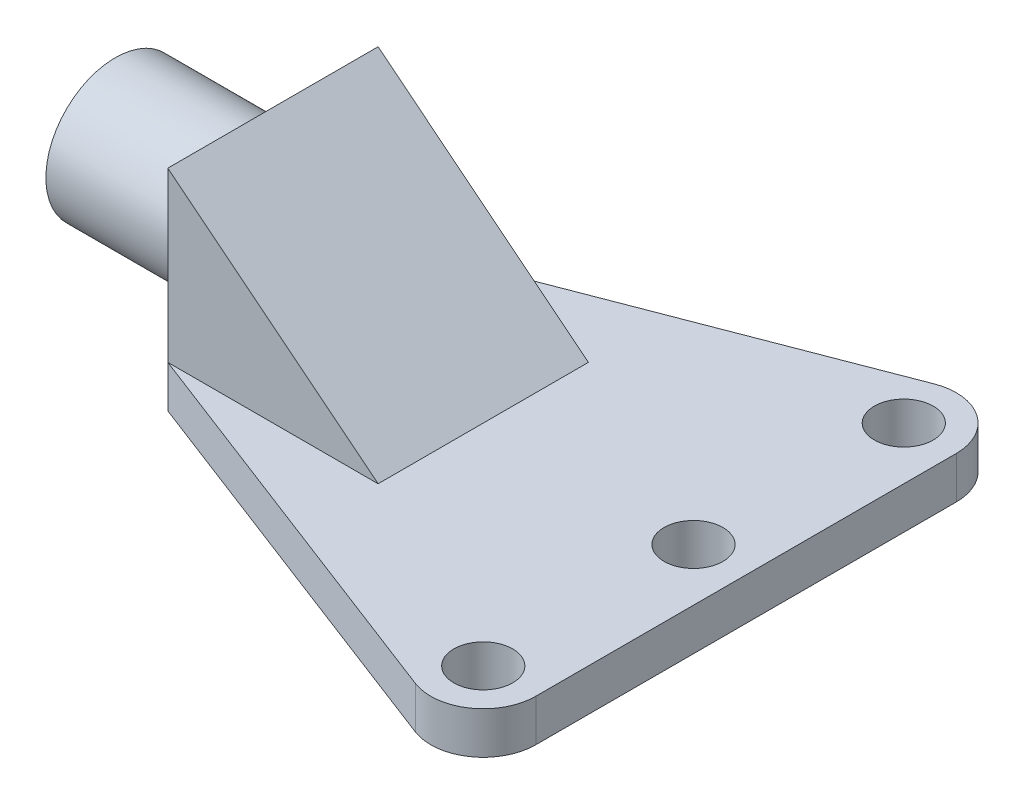
SolidWorks part; units mm, degrees
ref_plane "Front Plane" through (0, 0, 0) normal (0, 0, 1) x (1, 0, 0)
ref_plane "Top Plane" through (0, 0, 0) normal (0, 1, 0) x (1, 0, 0)
ref_plane "Right Plane" through (0, 0, 0) normal (1, 0, 0) x (0, 0, -1)
sketch "Sketch1" plane through (0, 0, 0) normal (0, 1, 0) x (1, 0, 0)
  line L0 (0, 0) -> (0, 25.4)
  line L1 (0, 0) -> (0, -25.4)
  line L2 (0, 0) -> (-38.1, 0)
  line L3 (-50.8, -12.7) -> (-2.2757, -31.3279)
  line L4 (-50.8, -12.7) -> (-25.4, -12.7)
  line L5 (-50.8, -12.7) -> (-50.8, 12.7)
  line L6 (-50.8, 12.7) -> (-25.4, 12.7)
  line L7 (-25.4, -12.7) -> (-25.4, 12.7)
  line L8 (-50.8, -12.7) -> (-25.4, 12.7) construction
  line L9 (-50.8, 12.7) -> (-25.4, -12.7) construction
  line L10 (-50.8, 12.7) -> (-2.2758, 31.3282)
  line L11 (0, 25.4) -> (6.35, 25.4)
  line L12 (6.35, 25.4) -> (6.3497, -25.4)
  circle A0 centre (0, 25.4) radius 3.302
  circle A1 centre (0, -25.4) radius 3.302
  arc A2 (-2.2757, -31.3279) -> (6.3497, -25.4) centre (0, -25.4) ccw
  arc A3 (6.35, 25.4) -> (-2.2758, 31.3282) centre (0, 25.4) ccw
sketch "Sketch2" plane through (0, 0, 0) normal (0, 1, 0) x (1, 0, 0)
  line L0 (-50.8, -12.7) -> (-25.4, -12.7)
  line L1 (-50.8, -12.7) -> (-50.8, 12.7)
  line L2 (-50.8, 12.7) -> (-25.4, 12.7)
  line L3 (-25.4, -12.7) -> (-25.4, 12.7)
extrude "Boss-Extrude1" add sketch "Sketch2" along normal blind 25.4
sketch "Sketch4" plane through (0, 0, 0) normal (0, 1, 0) x (1, 0, 0)
  line L0 (-50.8, -12.7) -> (-2.2757, -31.3279)
  line L1 (-50.8, -12.7) -> (-50.8, 12.7)
  line L2 (-50.8, 12.7) -> (-2.2758, 31.3282)
  line L3 (6.35, 25.4) -> (6.3497, -25.4)
  arc A0 (-2.2757, -31.3279) -> (6.3497, -25.4) centre (0, -25.4) ccw
  arc A1 (6.35, 25.4) -> (-2.2758, 31.3282) centre (0, 25.4) ccw
extrude "Boss-Extrude2" add sketch "Sketch4" along normal blind 5.08 separate body
sketch "Sketch5" plane through (0, 0, 0) normal (0, 1, 0) x (1, 0, 0)
  circle A0 centre (0, -25.4) radius 3.556
extrude "Cut-Extrude1" cut sketch "Sketch5" along normal up to next (5.08 mm away)
sketch "Sketch6" plane through (0, 0, 0) normal (0, 1, 0) x (1, 0, 0)
  circle A0 centre (0, 25.4) radius 3.556
extrude "Cut-Extrude2" cut sketch "Sketch6" along normal up to next (5.08 mm away)
sketch "Sketch7" plane through (0, 0, -12.7) normal (0, 0, -1) x (-1, 0, 0)
  line L0 (50.8, 25.4) -> (25.4, 5.08)
  line L1 (25.4, 25.4) -> (25.4, 0) construction
  line L2 (50.8, 5.08) -> (2.2757, 5.08) construction
  line L3 (25.4, 5.08) -> (25.4, 25.4)
  line L4 (25.4, 25.4) -> (50.8, 25.4)
sketch "Sketch8" plane through (0, 0, -12.7) normal (0, 0, -1) x (-1, 0, 0)
  line L0 (50.8, 25.4) -> (25.4, 5.08)
  line L1 (25.4, 5.08) -> (25.4, 25.4)
  line L2 (25.4, 25.4) -> (50.8, 25.4)
extrude "Cut-Extrude3" cut sketch "Sketch8" against normal up to next (25.4 mm away)
sketch "Sketch9" plane through (-50.8, 0, 0) normal (-1, 0, 0) x (0, 0, 1)
  line L0 (0, 25.4) -> (0, 0)
  line L1 (-12.7, 25.4) -> (12.7, 25.4) construction
  circle A0 centre (0, 12.7) radius 9.525
sketch "Sketch10" plane through (-50.8, 0, 0) normal (-1, 0, 0) x (0, 0, 1)
  circle A0 centre (0, 12.7) radius 8.382
extrude "Boss-Extrude3" add sketch "Sketch10" along normal blind 19.05
sketch "Sketch11" plane through (0, 0, 0) normal (0, 1, 0) x (1, 0, 0)
  circle A0 centre (0, 0) radius 3.302
sketch "Sketch12" plane through (0, 0, 0) normal (0, 1, 0) x (1, 0, 0)
  circle A0 centre (0, 0) radius 3.556
extrude "Cut-Extrude4" cut sketch "Sketch12" along normal up to next
